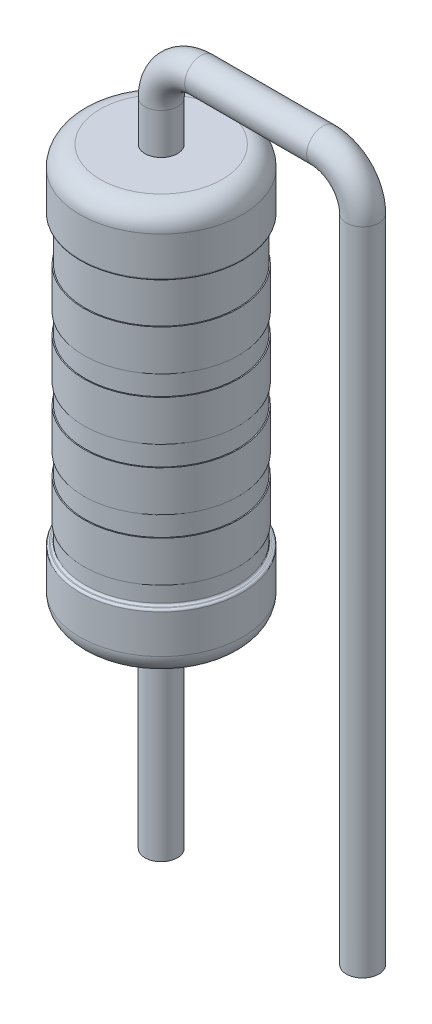
SolidWorks part; units mm, degrees
material "Alliage 2018"
ref_plane "Plan de face" through (0, 0, 0) normal (0, 0, 1) x (1, 0, 0)
ref_plane "Plan de dessus" through (0, 0, 0) normal (0, 1, 0) x (1, 0, 0)
ref_plane "Plan de droite" through (0, 0, 0) normal (1, 0, 0) x (0, 0, -1)
sketch "Esquisse1" plane through (0, 0, 0) normal (0, 0, 1) x (1, 0, 0)
  line L0 (0, -10) -> (0, 10) construction
  line L1 (-2, 3.55) -> (-2, 4.5)
  line L2 (-1.5, -5) -> (0, -5)
  line L3 (-2, -4.5) -> (-2, -3.55)
  line L4 (-1.5, 5) -> (0, 5)
  line L5 (0, 5) -> (0, -5)
  line L6 (-2, -5) -> (2, 5) construction
  line L7 (-2, 5) -> (2, -5) construction
  line L8 (-1.925, -3.5) -> (-1.95, -3.5)
  line L9 (-1.875, -3.45) -> (-1.875, 3.45)
  line L10 (-1.925, 3.5) -> (-1.95, 3.5)
  line L12 (-1.875, -3.5) -> (-2.125, 3.5) construction
  line L13 (-1.875, 3.5) -> (-2.1785, -4.9983) construction
  arc A0 (-1.95, -3.5) -> (-2, -3.55) centre (-1.95, -3.55) ccw
  arc A1 (-1.925, -3.5) -> (-1.875, -3.45) centre (-1.925, -3.45) ccw
  arc A3 (-1.875, 3.45) -> (-1.925, 3.5) centre (-1.925, 3.45) ccw
  arc A4 (-2, 3.55) -> (-1.95, 3.5) centre (-1.95, 3.55) ccw
  arc A6 (-2, -4.5) -> (-1.5, -5) centre (-1.5, -4.5) ccw
  arc A7 (-2, 4.5) -> (-1.5, 5) centre (-1.5, 4.5) cw
  point P0 (0, 0)
  point P4 (0, 0)
  point P9 (-2, 0)
  dimension "D6" = 0.05
  dimension "D8" = 0.5
  dimension "D1" = 20
  dimension "D2" = 10
  dimension "D3" = 4
  dimension "D4" = 0.25
  dimension "D5" = 1.5
  dimension "D7" = 1.5
revolve "Révolution1" add sketch "Esquisse1" angle 360 about L5
sketch "Esquisse2" plane through (0, -5, 0) normal (0, -1, 0) x (1, 0, 0)
  circle A0 centre (0, 0) radius 0.4
extrude "Boss.-Extru.1" add sketch "Esquisse2" along normal blind 5
sketch "Esquisse3" plane through (0, 5, 0) normal (0, 1, 0) x (1, 0, 0)
  circle A0 centre (0, 0) radius 0.4
sketch "Esquisse4" plane through (0, 0, 0) normal (0, 0, 1) x (1, 0, 0)
  line L0 (0.4, 5) -> (-0.4, 5) construction
  line L1 (4.9771, 5) -> (-0.4, 5) construction
  line L2 (-0.0229, 5) -> (-0.0229, 6)
  line L3 (0.9771, 7) -> (3.9771, 7)
  line L4 (4.9771, 6) -> (4.9771, -10)
  line L5 (-0.4, -10) -> (0.4, -10) construction
  line L6 (-0.4, -10) -> (4.9771, -10) construction
  arc A0 (3.9771, 7) -> (4.9771, 6) centre (3.9771, 6) cw
  arc A1 (-0.0229, 6) -> (0.9771, 7) centre (0.9771, 6) cw
  point P0 (6.3271, -11.3905)
  point P9 (4.9771, 7)
  point P10 (9.2735, -10)
  point P12 (9.6777, 5)
  point P17 (-0.0229, 7)
  dimension "D3" = 1
  dimension "D1" = 5
  dimension "D2" = 2
sweep "Balayage1" add profiles "Esquisse3" path "Esquisse4"
sketch "Esquisse5" plane through (0, 0, 0) normal (0, 0, 1) x (1, 0, 0)
  line L0 (-1.875, 3.45) -> (-1.875, -3.45) construction
  line L1 (-1.85, 2.45) -> (-1.9, 2.45)
  line L2 (-1.85, 2.45) -> (-1.85, 1.45)
  line L3 (-1.85, 1.45) -> (-1.9, 1.45)
  line L4 (-1.9, 2.45) -> (-1.9, 1.45)
  line L5 (-1.85, 2.45) -> (-1.9, 1.45) construction
  line L6 (-1.85, 1.45) -> (-1.9, 2.45) construction
  line L7 (1.875, 3.45) -> (-1.875, 3.45) construction
  line L8 (-1.85, 0.95) -> (-1.9, 0.95)
  line L9 (-1.85, 0.95) -> (-1.85, -0.05)
  line L10 (-1.85, -0.05) -> (-1.9, -0.05)
  line L11 (-1.9, 0.95) -> (-1.9, -0.05)
  line L12 (-1.85, 0.95) -> (-1.9, -0.05) construction
  line L13 (-1.85, -0.05) -> (-1.9, 0.95) construction
  line L14 (-1.85, -0.55) -> (-1.9, -0.55)
  line L15 (-1.85, -0.55) -> (-1.85, -1.55)
  line L16 (-1.85, -1.55) -> (-1.9, -1.55)
  line L17 (-1.9, -0.55) -> (-1.9, -1.55)
  line L18 (-1.85, -0.55) -> (-1.9, -1.55) construction
  line L19 (-1.85, -1.55) -> (-1.9, -0.55) construction
  line L20 (-1.85, -2.05) -> (-1.9, -2.05)
  line L21 (-1.85, -2.05) -> (-1.85, -3.05)
  line L22 (-1.85, -3.05) -> (-1.9, -3.05)
  line L23 (-1.9, -2.05) -> (-1.9, -3.05)
  line L24 (-1.85, -2.05) -> (-1.9, -3.05) construction
  line L25 (-1.85, -3.05) -> (-1.9, -2.05) construction
  line L26 (0, 5.0266) -> (0, -5) construction
  line L27 (-0.4, -5) -> (0.4, -5) construction
  point P0 (-1.875, 1.95)
  point P10 (-1.875, 0.45)
  point P15 (-1.875, -1.05)
  point P20 (-1.875, -2.55)
  dimension "D1" = 1
  dimension "D2" = 1
  dimension "D3" = 0.05
  dimension "D4" = 4
revolve "Révolution2" add sketch "Esquisse5" angle 360 about L26
